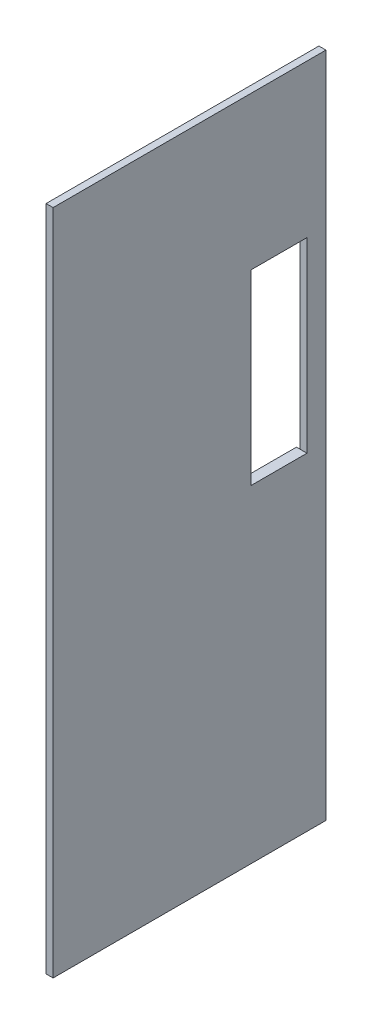
SolidWorks part; units mm, degrees
ref_plane "Спереди" through (0, 0, 0) normal (0, 0, 1) x (1, 0, 0)
ref_plane "Сверху" through (0, 0, 0) normal (0, 1, 0) x (1, 0, 0)
ref_plane "Справа" through (0, 0, 0) normal (1, 0, 0) x (0, 0, -1)
ref_plane "Плоскость4" through (0.5, 0, 0) normal (-1, 0, 0) x (0, -1, 0)
sketch "Эскиз1" plane through (0.5, 0, 0) normal (-1, 0, 0) x (0, -1, 0)
  line L0 (-5.85, 42.25) -> (-100.85, 42.25)
  line L1 (-100.85, 42.25) -> (-100.85, 3.4)
  line L2 (-100.85, 3.4) -> (-5.85, 3.4)
  line L3 (-5.85, 3.4) -> (-5.85, 42.25)
extrude "Бобышка-Вытянуть1" add sketch "Эскиз1" against normal blind 1
sketch "Эскиз2" plane through (0.5, 0, 0) normal (-1, 0, 0) x (0, 0, 1)
  line L0 (39.55, 8.55) -> (6.1, 8.55)
  line L1 (6.1, 8.55) -> (6.1, 98.15)
  line L2 (6.1, 98.15) -> (39.55, 98.15)
  line L3 (39.55, 98.15) -> (39.55, 8.55)
extrude "Бобышка-Вытянуть2" add sketch "Эскиз2" along normal blind 0.5
sketch "Эскиз3" plane through (0, 0, 0) normal (-1, 0, 0) x (0, 0, 1)
  line L0 (6.1, 98.15) -> (6.1, 8.55) construction
  line L1 (14.0542, 52.4873) -> (6.1, 52.4873)
  line L2 (14.0542, 52.4873) -> (14.0542, 79.0742)
  line L3 (14.0542, 79.0742) -> (6.1, 79.0742)
  line L4 (6.1, 52.4873) -> (6.1, 79.0742)
extrude "Вырез-Вытянуть1" cut sketch "Эскиз3" against normal blind 2
